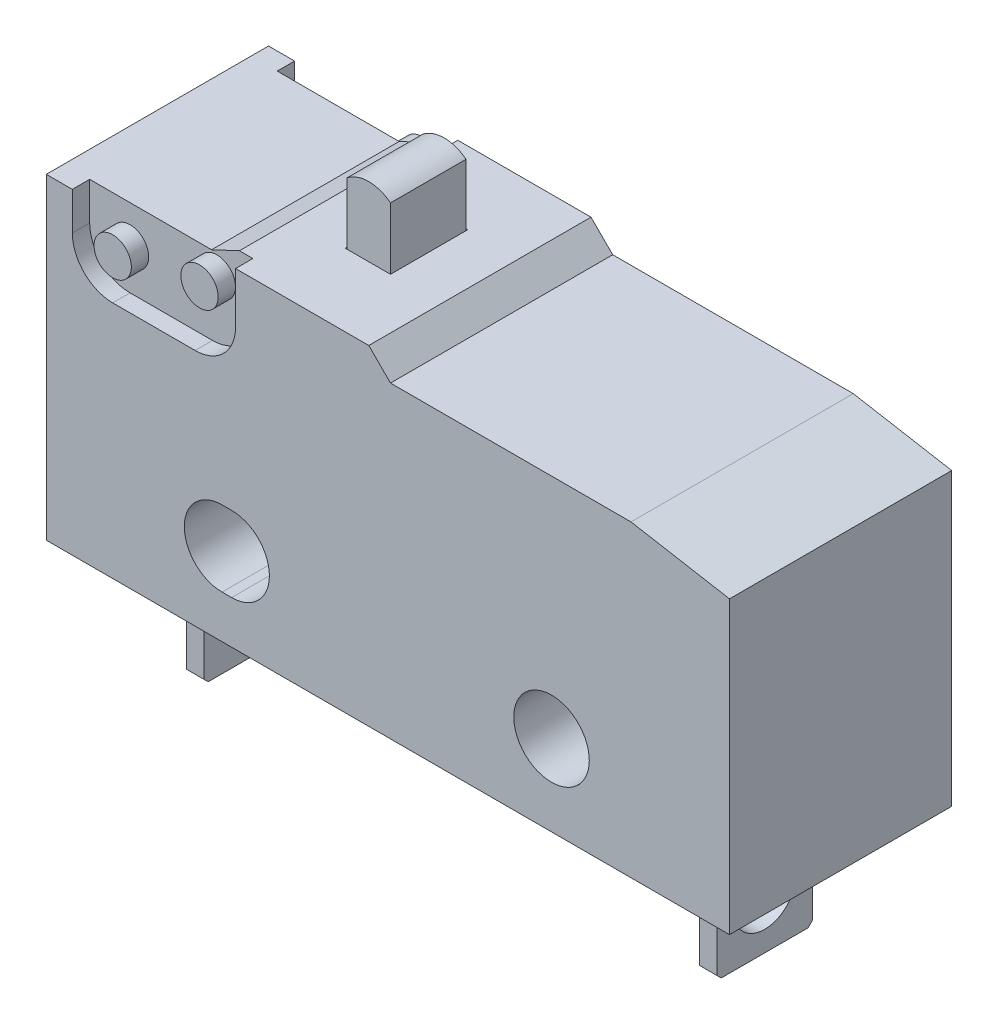
SolidWorks part; units mm, degrees
material "ABS"
ref_plane "Front" through (0, 0, 0) normal (0, 0, 1) x (1, 0, 0)
ref_plane "Top" through (0, 0, 0) normal (0, 1, 0) x (1, 0, 0)
ref_plane "Right" through (0, 0, 0) normal (1, 0, 0) x (0, 0, -1)
sketch "Sketch2" plane through (0, 0, 0) normal (0, 0, 1) x (1, 0, 0)
  line L0 (-4.8514, 3.4671) -> (-4.572, 3.4671)
  line L1 (9.9949, 8.509) -> (7.1139, 9.017)
  line L2 (-9.9949, 9.271) -> (-9.9949, 0)
  line L3 (-9.9949, 0) -> (9.9949, 0)
  line L4 (9.9949, 8.509) -> (9.9949, 0)
  line L5 (-4.8514, 1.2573) -> (-4.572, 1.2573)
  line L6 (-4.7117, 3.4671) -> (-4.7117, 1.2573) construction
  line L7 (4.7879, 2.3622) -> (-4.572, 2.3622) construction
  line L8 (7.1139, 9.017) -> (0.0762, 9.017)
  line L9 (0.0762, 9.017) -> (-0.5588, 9.652)
  line L10 (-0.5588, 9.652) -> (-4.8514, 9.652)
  line L11 (-4.8514, 9.652) -> (-5.6646, 9.271)
  line L12 (-5.6646, 9.271) -> (-9.9949, 9.271)
  line L13 (-2.7051, 9.652) -> (-2.7051, 2.3622) construction
  line L14 (-4.8514, 9.652) -> (-4.8514, 3.4671) construction
  circle A0 centre (4.7879, 2.3622) radius 1.1049
  arc A1 (-4.8514, 3.4671) -> (-4.8514, 1.2573) centre (-4.8514, 2.3622) ccw
  arc A2 (-4.572, 1.2573) -> (-4.572, 3.4671) centre (-4.572, 2.3622) ccw
  dimension "D4" = 5.207
  dimension "D5" = 2.2098
  dimension "D6" = 2.4892
  dimension "D7" = 6.6548
  dimension "D8" = 7.2898
  dimension "D9" = 7.493
  dimension "D13" = 6.9088
  dimension "D1" = 19.9898
  dimension "D2" = 2.3622
  dimension "D3" = 9.4996
  dimension "D10" = 0.508
  dimension "D11" = 10
  dimension "D12" = 135
extrude "Extrude1" add sketch "Sketch2" along normal mid plane 6.5024
sketch "Sketch3" plane through (0, 0, 0) normal (0, 0, 1) x (1, 0, 0)
  line L0 (-3.3401, 9.271) -> (-3.3401, 11.4357)
  line L1 (-2.7051, 9.271) -> (-2.7051, 10.6426) construction
  line L2 (-2.0701, 11.4357) -> (-2.0701, 9.271)
  line L3 (-2.0701, 9.271) -> (-3.3401, 9.271)
  line L4 (-3.3401, 11.4357) -> (-2.0701, 11.4357) construction
  line L5 (-2.7051, 9.652) -> (-2.7051, 2.3622) construction
  line L6 (-5.6646, 9.271) -> (-9.9949, 9.271) construction
  arc A0 (-3.3401, 11.4357) -> (-2.0701, 11.4357) centre (-2.7051, 10.6426) cw
  arc A1 (-4.8514, 3.4671) -> (-4.8514, 1.2573) centre (-4.8514, 2.3622) ccw construction
  dimension "D1" = 9.2964
  dimension "D3" = 1.016
  dimension "D2" = 1.27
extrude "Extrude2" add sketch "Sketch3" along normal mid plane 2.2098 separate body
sketch "Sketch4" plane through (0, 9.652, 0) normal (0, 1, 0) x (-1, 0, 0)
  line L0 (2.0701, -1.1049) -> (3.3401, -1.1049) construction
  line L1 (3.3401, 1.1049) -> (3.3401, -1.1049) construction
  line L2 (2.0701, 1.1049) -> (2.0701, -1.1049) construction
  line L3 (3.3401, 1.1049) -> (2.0701, 1.1049) construction
  line L4 (2.0701, -1.1049) -> (3.3401, -1.1049) construction
  line L5 (3.3401, 1.1049) -> (3.3401, -1.1049) construction
  line L6 (2.0701, 1.1049) -> (2.0701, -1.1049) construction
  line L7 (3.3401, 1.1049) -> (2.0701, 1.1049) construction
  line L8 (3.3655, 1.1303) -> (3.3655, -1.1303)
  line L9 (2.0447, -1.1303) -> (3.3655, -1.1303)
  line L10 (2.0447, 1.1303) -> (2.0447, -1.1303)
  line L11 (3.3655, 1.1303) -> (2.0447, 1.1303)
  dimension "D1" = 0.0254
extrude "Cut-Extrude1" cut sketch "Sketch4" against normal blind 1.016
sketch "Sketch5" plane through (0, 0, 3.2512) normal (0, 0, 1) x (1, 0, 0)
  line L0 (-9.2329, 9.271) -> (-9.2329, 8.1661)
  line L1 (-8.0518, 6.985) -> (-5.6388, 6.985)
  line L2 (-4.4577, 8.1661) -> (-4.4577, 9.652)
  line L3 (-5.6646, 9.271) -> (-9.9949, 9.271) construction
  line L4 (-4.8514, 9.652) -> (-5.6646, 9.271) construction
  line L5 (-0.5588, 9.652) -> (-4.8514, 9.652) construction
  line L6 (-5.6646, 9.271) -> (-9.2329, 9.271)
  line L7 (-4.8514, 9.652) -> (-5.6646, 9.271)
  line L8 (-4.4577, 9.652) -> (-4.8514, 9.652)
  line L9 (-9.9949, 9.271) -> (-9.9949, 0) construction
  circle A0 centre (-5.5118, 8.6741) radius 0.5461
  circle A1 centre (-8.0518, 8.1661) radius 0.5461
  arc A2 (-9.2329, 8.1661) -> (-8.0518, 6.985) centre (-8.0518, 8.1661) ccw
  arc A3 (-5.6388, 6.985) -> (-4.4577, 8.1661) centre (-5.6388, 8.1661) ccw
  dimension "D4" = 0.0508
  dimension "D5" = 1.0922
  dimension "D6" = 2.54
  dimension "D7" = 0.508
  dimension "D1" = 0.762
  dimension "D2" = 0.508
  dimension "D3" = 0.635
extrude "Cut-Extrude2" cut sketch "Sketch5" against normal blind 0.508
mirror "Mirror1" about plane through (0, 0, 0) normal (0, 0, 1) of "Cut-Extrude2"
ref_plane "Plane1" through (-7.493, 0, 0) normal (1, 0, 0) x (0, 0, -1)
sketch "Sketch10" plane through (-7.493, 0, 0) normal (1, 0, 0) x (0, 0, -1)
  line L0 (-1.397, 0) -> (-1.397, -3.0734)
  line L1 (-1.27, -3.2004) -> (1.27, -3.2004)
  line L2 (1.397, -3.0734) -> (1.397, 0)
  line L3 (1.397, 0) -> (-1.397, 0)
  line L4 (0, -3.2004) -> (0, -1.7018) construction
  line L5 (0, 0) -> (0, -1.7018) construction
  line L6 (-1.397, -3.0734) -> (-1.27, -3.2004)
  line L7 (1.27, -3.2004) -> (1.397, -3.0734)
  circle A0 centre (0, -1.7018) radius 0.9017
  point P1 (-1.397, -3.2004)
  point P3 (1.397, -3.2004)
  dimension "D2" = 1.8034
  dimension "D1" = 3.2004
  dimension "D3" = 2.794
  dimension "D4" = 1.4986
  dimension "D5" = 0.127
  dimension "D6" = 45
  dimension "D7" = 0.127
  dimension "D8" = 45
extrude "Extrude6" add sketch "Sketch10" along normal mid plane 0.508
pattern_linear "LPattern1" count 2 spacing 15.0114 along (1, 0, 0) of "Extrude6"
